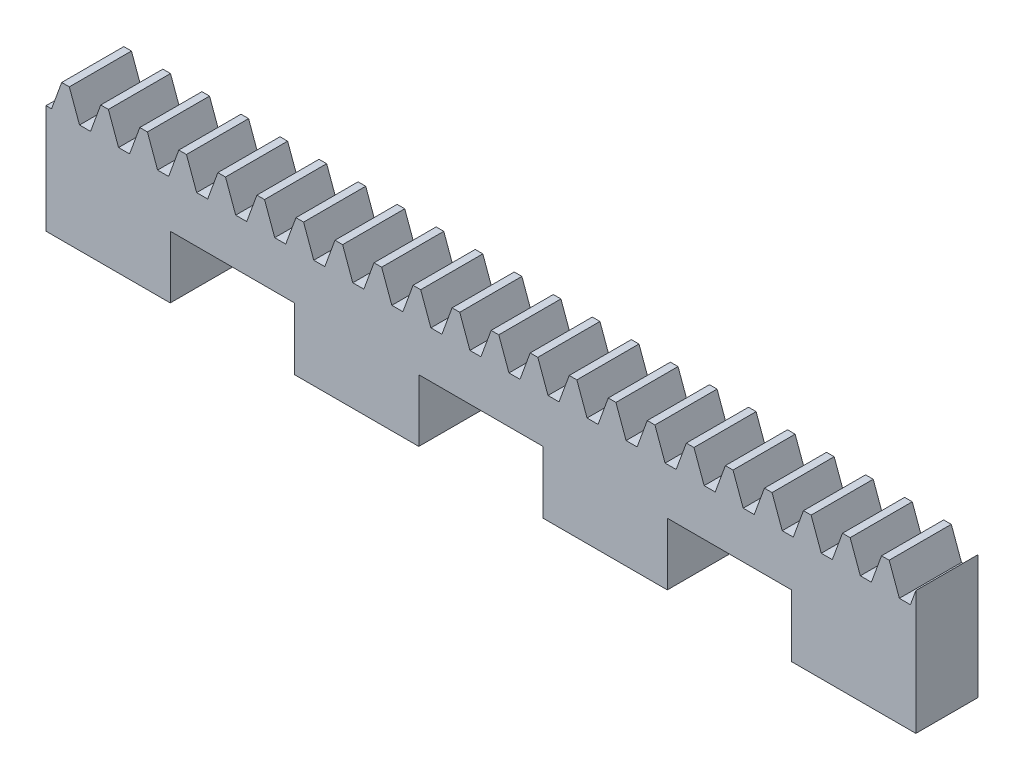
SolidWorks part; units mm, degrees
extrude "Blank" add sketch "BlankSke" against normal blind 5
sketch "BlankSke" plane through (0, 0, 0) normal (0, 0, 1) x (1, 0, 0)
  line L1 (0, 0) -> (70, 0)
  line L2 (0, 0) -> (0, 11)
  line L3 (0, 11) -> (70, 11)
  line L4 (70, 0) -> (70, 11)
  dimension "Length" = 70
  dimension "Blank_height" = 11
material "ﾁｰｸ材"
ref_plane "Plane1" through (0, 0, 0) normal (0, 0, 1) x (1, 0, 0)
ref_plane "Plane2" through (0, 0, 0) normal (0, 1, 0) x (1, 0, 0)
ref_plane "Plane3" through (0, 0, 0) normal (1, 0, 0) x (0, 0, -1)
sketch "HoldingSke" plane through (0, 0, 0) normal (0, 1, 0) x (1, 0, 0)
  line L0 (0, 0) -> (0.1392, 0.9903)
  line L1 (-15, 0) -> (100, 0) construction
  line L2 (0, 0) -> (-2.1039, 2.3779)
  line L3 (0, 0) -> (-11.863, 4.5341)
  line L4 (0, 0) -> (7.8894, 3.5126)
  line L5 (0, 0) -> (-23.7986, -8.8762)
  line L6 (0, 0) -> (-10.5278, -7.1032)
  line L9 (-71.009, 38.7566) -> (-5.2305, 62.698)
  line L10 (-76.2, 3.3779) -> (-66.2, 3.3779)
  line L11 (0, 0) -> (-5, 0)
  line L12 (-76.2, 101.6) -> (-76.162, 101.6)
  line L13 (24.9733, 27.94) -> (52.9518, 28.4284)
  line L14 (24.9733, 27.94) -> (24.9743, 27.94)
  line L15 (24.9733, 27.94) -> (100.4006, 29.5858)
  circle A0 centre (0, 0) radius 19.05
  circle A1 centre (0, 0) radius 5
  circle A2 centre (0, 0) radius 12.7
  dimension "MPH" = 10
  dimension "Diameter" = 38.1
  dimension "Num_teeth" = 24
  dimension "Pitch" = 1
  dimension "Show_teeth" = 998
  dimension "Thickness" = 12.7
  dimension "Ap" = 20
  dimension "Pitch_height" = 10
  dimension "Width" = 5
  dimension "Backlash" = 0.038
  dimension "Addendum_fac" = 1
  dimension "Dedendum_fac" = 1.25
  dimension "Clearance_fac" = 0.25
  dimension "Dedendum_add" = 0.001
  dimension "Length" = 70
  dimension "Module" = 1
sketch "TooCutSkeIll" plane through (0, 0, 0) normal (0, 0, 1) x (1, 0, 0)
  line L0 (-1.2538, 10.9737) -> (-0.5045, 8.9152)
  line L1 (-0.2687, 8.75) -> (0.2687, 8.75)
  line L2 (0.5045, 8.9152) -> (1.2538, 10.9737)
  line L3 (70, 11) -> (0, 11) construction
  line L4 (0, 0) -> (0, 64.897) construction
  line L5 (-13.208, 10) -> (12.954, 10) construction
  line L6 (0, 0) -> (70, 0) construction
  line L7 (0.8994, 10) -> (0.8994, 48.7463) construction
  line L8 (-0.8994, 10) -> (-0.8994, 48.7463) construction
  line L9 (1.2914, 11) -> (1.2914, 11.0254)
  line L10 (-1.2914, 11) -> (-1.2914, 11.0254)
  line L11 (-1.2914, 11.0254) -> (1.2914, 11.0254)
  arc A0 (0.2687, 8.75) -> (0.5045, 8.9152) centre (0.2687, 9.001) ccw
  arc A1 (-0.5045, 8.9152) -> (-0.2687, 8.75) centre (-0.2687, 9.001) ccw
  arc A2 (1.2914, 11) -> (1.2538, 10.9737) centre (1.2914, 10.96) ccw
  arc A3 (-1.2538, 10.9737) -> (-1.2914, 11) centre (-1.2914, 10.96) ccw
  dimension "Pitch_height" = 10
  dimension "Addendum_plus" = 1.0254
  dimension "Pressure_angle" = 20
  dimension "Gap_width" = 1.7988
  dimension "Dedendum" = 1.25
extrude "ToothCutIll" [suppressed] cut sketch "TooCutSkeIll" against normal through all
sketch "TooCutSkeSim" plane through (0, 0, 0) normal (0, 0, 1) x (1, 0, 0)
  line L0 (0.4444, 8.75) -> (-0.4444, 8.75)
  line L1 (1.2726, 11.0254) -> (0.4444, 8.75)
  line L2 (0, 17.4625) -> (0, 53.467) construction
  line L3 (1.2726, 11.0254) -> (-1.2726, 11.0254)
  line L6 (-1.2726, 11.0254) -> (-0.4444, 8.75)
  line L9 (-0.8994, 10) -> (0.8994, 10) construction
  line L10 (0, 0) -> (70, 0) construction
  line L11 (0.8994, 10) -> (0.8994, 53.467) construction
  line L12 (-0.8994, 10) -> (-0.8994, 53.467) construction
  dimension "Pitch_height" = 10
  dimension "Addendum_plus" = 1.0254
  dimension "Pressure_angle" = 20
  dimension "Gap_width" = 1.7988
  dimension "Dedendum" = 1.25
extrude "ToothCutSim" cut sketch "TooCutSkeSim" against normal through all
pattern_linear "TeethCuts" count 23 spacing 3.1416 along (1, 0, 0) of "ToothCutIll", "ToothCutSim"
sketch "ｽｹｯﾁ1" plane through (0, 0, 0) normal (0, 0, 1) x (1, 0, 0)
  line L0 (0, 0) -> (70, 0) construction
  line L1 (0, 8.75) -> (0, 0) construction
  line L2 (10, 0) -> (20, 0)
  line L3 (10, 0) -> (10, 5)
  line L4 (10, 5) -> (20, 5)
  line L5 (20, 0) -> (20, 5)
  line L6 (30, 0) -> (30, 5)
  line L7 (30, 0) -> (40, 0)
  line L8 (40, 0) -> (40, 5)
  line L9 (30, 5) -> (40, 5)
  line L10 (50, 0) -> (50, 5)
  line L11 (50, 0) -> (60, 0)
  line L12 (60, 0) -> (60, 5)
  line L13 (50, 5) -> (60, 5)
  dimension "D1" = 5
  dimension "D2" = 10
  dimension "D3" = 10
  dimension "D4" = 3
extrude "ｶｯﾄ - 押し出し1" cut sketch "ｽｹｯﾁ1" against normal through all
equation "' \"Module@HoldingSke\" = 6.35"
equation "' \"Num_teeth@HoldingSke\" = 12"
equation "' \"Ap@HoldingSke\" =  20"
equation "' \"Ap@HoldingSke\" = 20"
equation "' \"Width@HoldingSke\" = 0.25 * 25.4"
equation "' \"Show_teeth@HoldingSke\" = 500"
equation "' \"Backlash@HoldingSke\" = 0.009 * 25.4"
equation "' \"Addendum_fac@HoldingSke\" = 1.0"
equation "' \"Dedendum_fac@HoldingSke\" = 1.25"
equation "' \"Dedendum_add@HoldingSke\" = 0.00005 * 25.4"
equation "' \"Clearance_fac@HoldingSke\" = 0.25"
equation "' \"Pitch_height@HoldingSke\" = 1 * 25.4"
equation "' \"Length@HoldingSke\" = 4.71 * 25.4"
equation "\"Pitch@HoldingSke\" = 1 / \"Module@HoldingSke\""
equation "\"MPH@HoldingSke\" = \"Dedendum_fac@HoldingSke\" / \"Pitch@HoldingSke\" + 2 * \"Dedendum_add@HoldingSke\" + 0.002 * 25.4"
equation "\"MPH@HoldingSke\" = ((sgn( \"MPH@HoldingSke\" - \"Pitch_height@HoldingSke\")+1)*( \"MPH@HoldingSke\" - \"Pitch_height@HoldingSke\"))/2 + \"Pitch_height@HoldingSke\""
equation "\"Blank_height@BlankSke\" = \"Pitch_height@HoldingSke\" + \"Addendum_fac@HoldingSke\"  / \"Pitch@HoldingSke\" "
equation "\"Length@BlankSke\" =  \"Length@HoldingSke\""
equation "\"Face_width@Blank\" = \"Width@HoldingSke\""
equation "\"Pressure_angle@TooCutSkeIll\" = \"Ap@HoldingSke\""
equation "\"Addendum_plus@TooCutSkeIll\" =  \"Addendum_fac@HoldingSke\"  / \"Pitch@HoldingSke\" + 0.001 *25.4"
equation "\"Dedendum@TooCutSkeIll\" = \"Dedendum_fac@HoldingSke\"  / \"Pitch@HoldingSke\""
equation "\"Pitch_height@TooCutSkeIll\" =  \"MPH@HoldingSke\""
equation "\"Gap_width@TooCutSkeIll\" = 3.14159265 / 2 / \"Pitch@HoldingSke\" + 6 * \"Backlash@HoldingSke\""
equation "\"Pressure_angle@TooCutSkeSim\" = \"Ap@HoldingSke\""
equation "\"Addendum_plus@TooCutSkeSim\" =  \"Addendum_fac@HoldingSke\"  / \"Pitch@HoldingSke\" + 0.001 * 25.4"
equation "\"Dedendum@TooCutSkeSim\" = \"Dedendum_fac@HoldingSke\"  / \"Pitch@HoldingSke\""
equation "\"Pitch_height@TooCutSkeSim\" =  \"MPH@HoldingSke\""
equation "\"Gap_width@TooCutSkeSim\" = 3.14159265 / 2 / \"Pitch@HoldingSke\" + 6 * \"Backlash@HoldingSke\""
equation "\"Root_fillet@TooCutSkeIll\" = \"Clearance_fac@HoldingSke\" / \"Pitch@HoldingSke\" + \"Dedendum_add@HoldingSke\""
equation "\"Break_rad@TooCutSkeIll\" = 0.02 / \"Pitch@HoldingSke\" * 2"
equation "\"Linear_pitch@TeethCuts\" = 3.14159265 / \"Pitch@HoldingSke\""
equation "\"Num_teeth@HoldingSke\" = int( ( \"Length@HoldingSke\" + 0 ) / (3.14159265 / \"Pitch@HoldingSke\")) + 0.9999  + 1"
equation " \"Num_teeth@TeethCuts\" = int( \"Show_teeth@HoldingSke\" ) + 1"
equation " \"Num_teeth@TeethCuts\" = ((sgn( \"Num_teeth@TeethCuts\" - \"Num_teeth@HoldingSke\" )-1)*( \"Num_teeth@TeethCuts\" - \"Num_teeth@HoldingSke\" ))/-2+ \"Num_teeth@HoldingSke\""
equation " \"Num_teeth@TeethCuts\" = ((sgn( \"Num_teeth@TeethCuts\" - 2.0)+1)*( \"Num_teeth@TeethCuts\" - 2.0))/2 +2.0"
